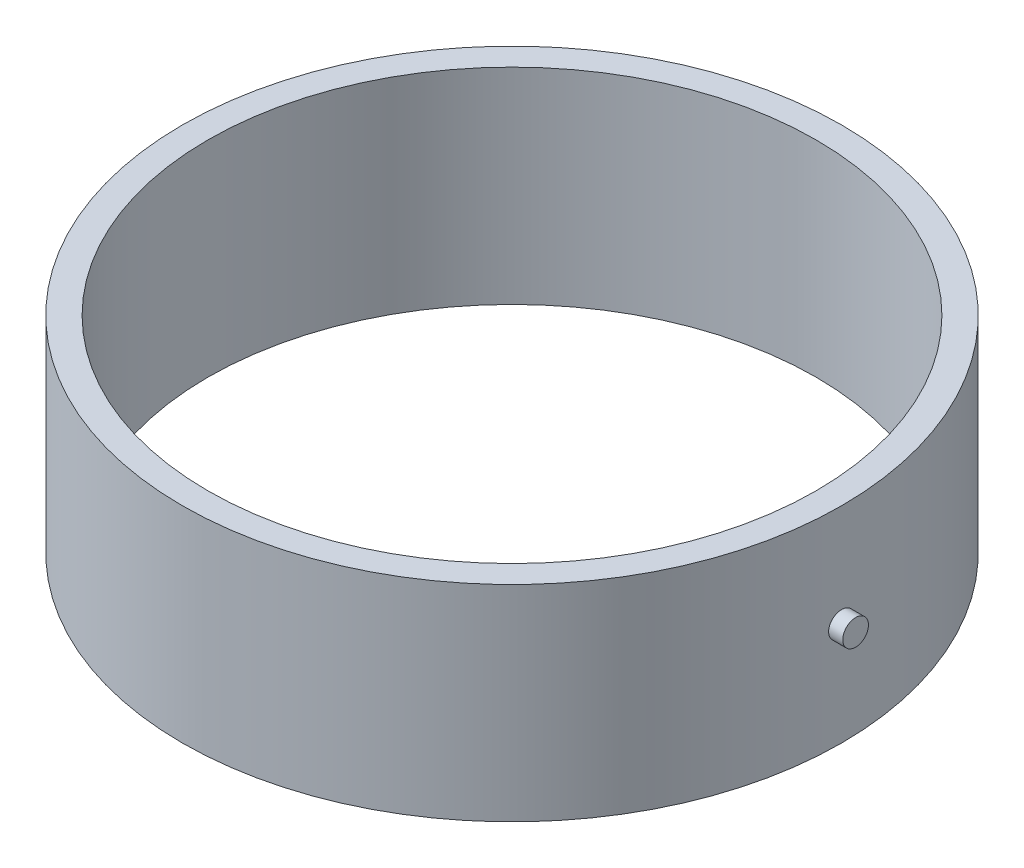
SolidWorks part; units mm, degrees
ref_plane "Front Plane" through (0, 0, 0) normal (0, 0, 1) x (1, 0, 0)
ref_plane "Top Plane" through (0, 0, 0) normal (0, 1, 0) x (1, 0, 0)
ref_plane "Right Plane" through (0, 0, 0) normal (1, 0, 0) x (0, 0, -1)
sketch "Sketch1" plane through (0, 0, 0) normal (0, 1, 0) x (1, 0, 0)
  circle A0 centre (0, 0) radius 1955.8
  circle A1 centre (0, 0) radius 1803.4
  dimension "D1" = 3911.6
  dimension "D2" = 3606.8
extrude "Boss-Extrude1" add sketch "Sketch1" along normal mid plane 1219.2
ref_plane "Plane1" through (-1955.8, 0, 0) normal (-1, 0, 0) x (0, 0, 1)
sketch "Sketch2" plane through (-1955.8, 0, 0) normal (-1, 0, 0) x (0, 0, 1)
  circle A0 centre (0, 0) radius 76.2
  dimension "D1" = 152.4
extrude "Boss-Extrude2" add sketch "Sketch2" along normal blind 82.55 and the other way blind 76.2
mirror "Mirror1" about plane through (0, 0, 0) normal (1, 0, 0) of "Boss-Extrude2"
